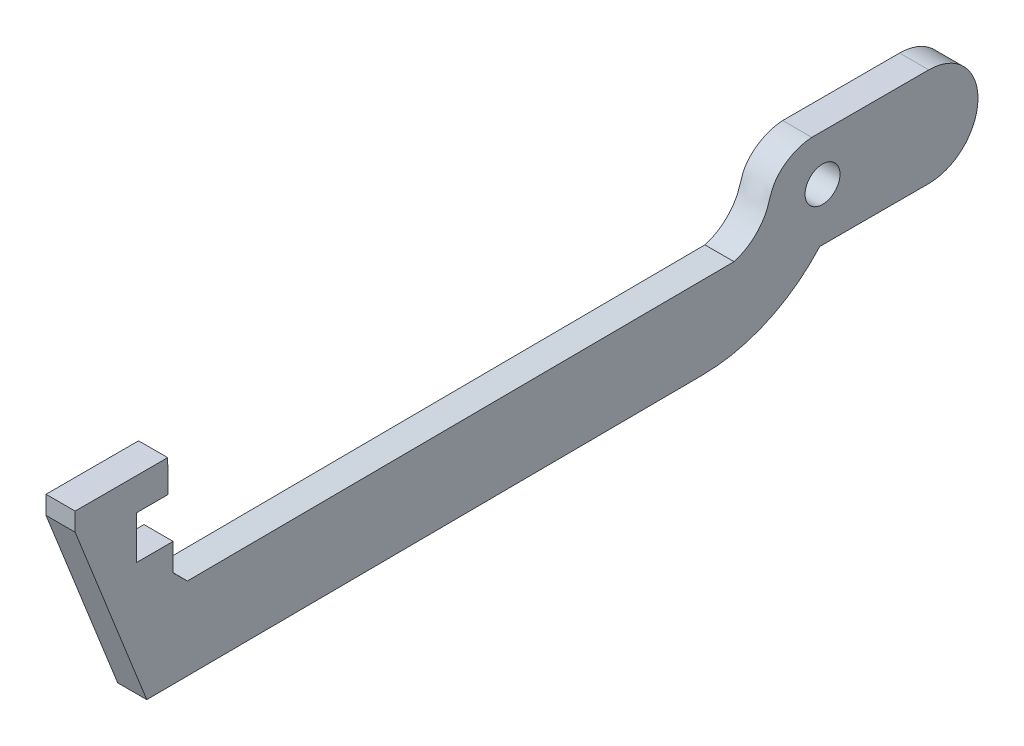
SolidWorks part; units mm, degrees
ref_plane "Front Plane" through (0, 0, 0) normal (0, 0, 1) x (1, 0, 0)
ref_plane "Top Plane" through (0, 0, 0) normal (0, 1, 0) x (1, 0, 0)
ref_plane "Right Plane" through (0, 0, 0) normal (1, 0, 0) x (0, 0, -1)
sketch "Sketch1" plane through (0, 0, 0) normal (1, 0, 0) x (0, 0, -1)
  line L0 (-50.0984, 7.0886) -> (-43.8491, -8.6836)
  line L1 (-43.8491, -8.6836) -> (4.6584, -8.3976)
  line L2 (14.8311, -3.804) -> (24.3341, -3.804)
  line L3 (24.3341, 4.7863) -> (14.1346, 4.7863)
  line L4 (7.3536, -1.2101) -> (-40.3051, -1.4911)
  line L5 (-40.3051, -1.4911) -> (-41.5534, -0.2574)
  line L6 (-41.5534, -0.2574) -> (-41.5534, 2.1222)
  line L7 (-41.5534, 2.1222) -> (-44.7661, 2.1222)
  line L8 (-44.7661, 2.1222) -> (-44.7661, 5.878)
  line L9 (-44.7661, 5.878) -> (-42.0087, 5.878)
  line L10 (-42.0087, 5.878) -> (-42.0252, 8.6836)
  line L11 (-42.0252, 8.6836) -> (-50.0984, 8.6836)
  line L12 (-50.0984, 8.6836) -> (-50.0984, 7.0886)
  arc A0 (4.6584, -8.3976) -> (14.8311, -3.804) centre (4.5774, 5.3426) ccw
  arc A1 (24.3341, -3.804) -> (24.3341, 4.7863) centre (24.3341, 0.4911) ccw
  circle A2 centre (15.0725, 0.7793) radius 1.524
  spline S0 degree 3 poles (14.1346, 4.7863) (12.8434, 4.7314) (10.814, 3.6608) (10.1659, 0.4805) (8.6134, -0.8576) (7.3536, -1.2101) knots 0 0 0 0 0.424423 0.587763 1 1 1 1
extrude "Boss-Extrude1" add sketch "Sketch1" along normal blind 2.54
